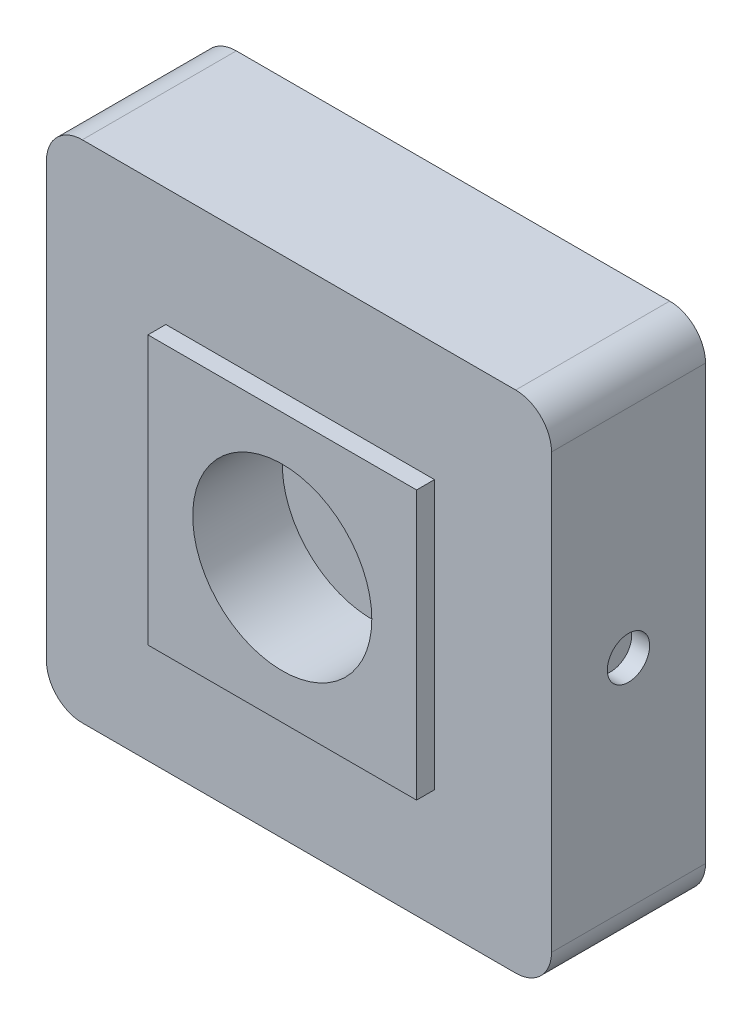
SolidWorks part; units mm, degrees
ref_plane "Front Plane" through (0, 0, 0) normal (0, 0, 1) x (1, 0, 0)
ref_plane "Top Plane" through (0, 0, 0) normal (0, 1, 0) x (1, 0, 0)
ref_plane "Right Plane" through (0, 0, 0) normal (1, 0, 0) x (0, 0, -1)
sketch "Sketch1" plane through (0, 0, 0) normal (0, 0, 1) x (1, 0, 0)
  line L1 (2.54, 0) -> (33.274, 0)
  line L2 (0, 2.54) -> (0, 33.274)
  line L3 (2.54, 35.814) -> (33.274, 35.814)
  line L4 (35.814, 2.54) -> (35.814, 33.274)
  arc A0 (2.54, 0) -> (0, 2.54) centre (2.54, 2.54) cw
  arc A1 (33.274, 0) -> (35.814, 2.54) centre (33.274, 2.54) ccw
  arc A2 (33.274, 35.814) -> (35.814, 33.274) centre (33.274, 33.274) cw
  arc A3 (0, 33.274) -> (2.54, 35.814) centre (2.54, 33.274) cw
  point P7 (0, 0)
  point P12 (35.814, 35.814)
  point P15 (0, 35.814)
  dimension "D3" = 2.54
  dimension "D1" = 35.814
  dimension "D2" = 35.814
extrude "Boss-Extrude1" add sketch "Sketch1" along normal blind 10.922
sketch "Sketch2" plane through (0, 0, 10.922) normal (0, 0, 1) x (1, 0, 0)
  line L0 (17.907, 35.814) -> (17.907, 0) construction
  line L1 (8.4654, 27.432) -> (27.5154, 27.432)
  line L2 (8.4654, 27.432) -> (8.4654, 8.382)
  line L3 (8.4654, 8.382) -> (27.5154, 8.382)
  line L4 (27.5154, 27.432) -> (27.5154, 8.382)
  line L5 (33.274, 35.814) -> (2.54, 35.814) construction
  line L6 (2.54, 0) -> (33.274, 0) construction
  line L7 (35.814, 17.907) -> (0, 17.907) construction
  line L8 (35.814, 2.54) -> (35.814, 33.274) construction
  line L9 (0, 33.274) -> (0, 2.54) construction
  dimension "D1" = 19.05
  dimension "D2" = 19.05
  dimension "D3" = 9.525
  dimension "D4" = 9.6084
extrude "Boss-Extrude2" add sketch "Sketch2" along normal blind 1.27
sketch "Sketch3" plane through (0, 0, 12.192) normal (0, 0, 1) x (1, 0, 0)
  circle A0 centre (17.9904, 17.907) radius 6.35
  dimension "D1" = 12.7
extrude "Cut-Extrude1" cut sketch "Sketch3" against normal blind 6.35
sketch "Sketch4" plane through (0, 0, 0) normal (-1, 0, 0) x (0, 0, 1)
  circle A0 centre (5.461, 17.907) radius 1.5
  dimension "D1" = 3
sketch "Sketch5" plane through (35.814, 0, 0) normal (1, 0, 0) x (0, 0, -1)
  circle A0 centre (-5.461, 17.907) radius 1.5
  dimension "D1" = 3
extrude "Cut-Extrude2" cut sketch "Sketch4" against normal blind 1.27
extrude "Cut-Extrude3" cut sketch "Sketch5" against normal blind 1.27
